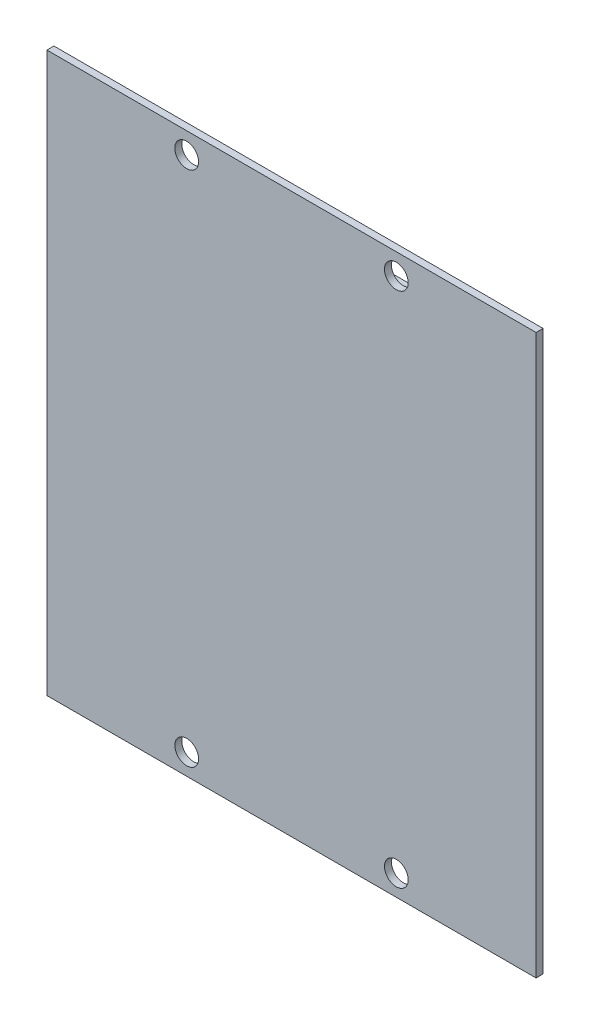
SolidWorks part; units mm, degrees
ref_plane "Front Plane" through (0, 0, 0) normal (0, 0, 1) x (1, 0, 0)
ref_plane "Top Plane" through (0, 0, 0) normal (0, 1, 0) x (1, 0, 0)
ref_plane "Right Plane" through (0, 0, 0) normal (1, 0, 0) x (0, 0, -1)
sketch "Sketch1" plane through (0, 0, 0) normal (0, 0, 1) x (1, 0, 0)
  line L1 (-35, -40) -> (35, -40)
  line L2 (-35, -40) -> (-35, 40)
  line L3 (-35, 40) -> (35, 40)
  line L4 (35, -40) -> (35, 40)
  line L5 (-35, -40) -> (35, 40) construction
  line L6 (-35, 40) -> (35, -40) construction
  point P0 (0, 0)
extrude "Boss-Extrude1" add sketch "Sketch1" against normal blind 1
ref_plane "Plane_1" through (0, 0, 0) normal (0, 0, 1) x (1, 0, 0)
sketch "Sketch2" plane through (0, 0, 0) normal (0, 0, 1) x (1, 0, 0)
  line L1 (-22.75, -24) -> (22.75, -24)
  line L2 (-22.75, -24) -> (-22.75, 24)
  line L3 (-22.75, 24) -> (22.75, 24)
  line L4 (22.75, -24) -> (22.75, 24)
  line L5 (-22.75, -24) -> (22.75, 24) construction
  line L6 (-22.75, 24) -> (22.75, -24) construction
  point P0 (0, 0)
extrude "Boss-Extrude2" add sketch "Sketch2" against normal blind 13
sketch "Sketch3" plane through (0, 0, 0) normal (0, 0, 1) x (1, 0, 0)
  circle A0 centre (-15, -37) radius 1.7
  circle A1 centre (-15, 37) radius 1.7
  circle A2 centre (15, -37) radius 1.7
  circle A3 centre (15, 37) radius 1.7
extrude "Lo_M3_bat_driver" cut sketch "Sketch3" along normal through all and the other way through all
